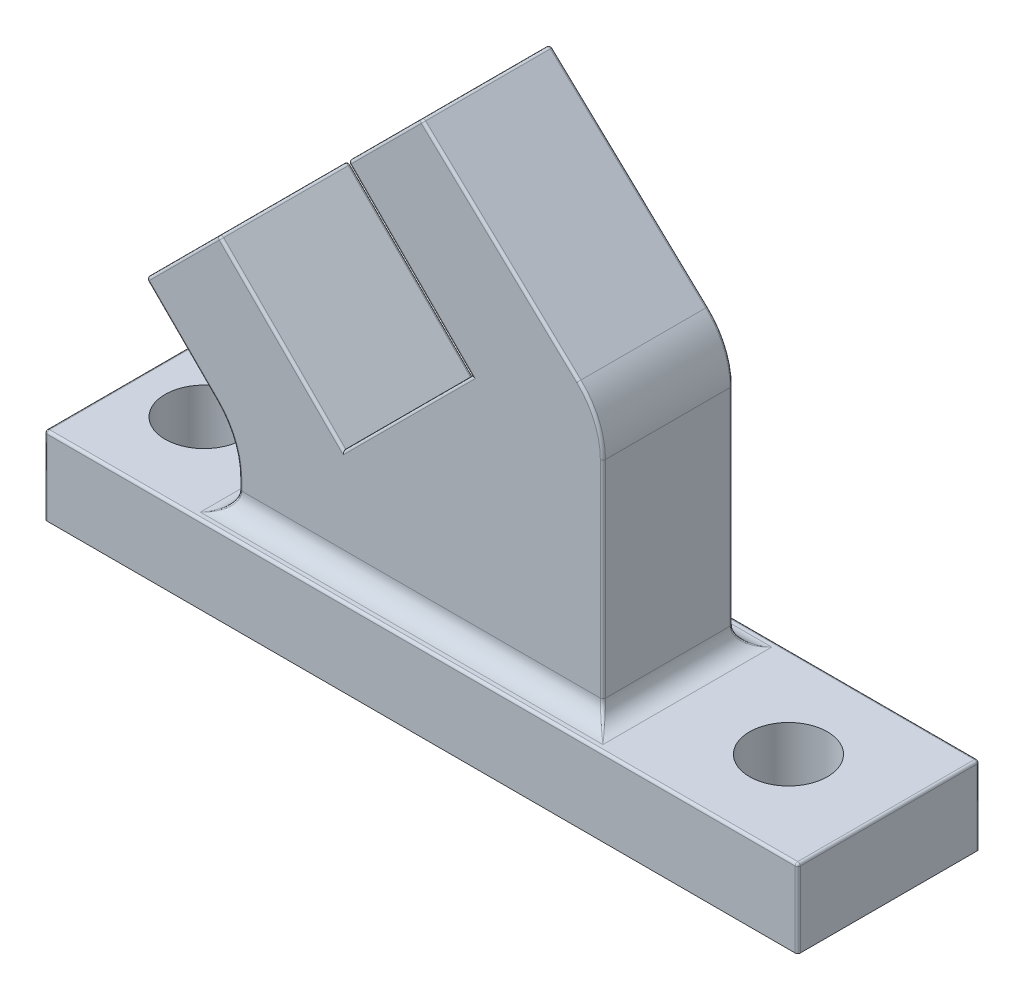
SolidWorks part; units mm, degrees
material "6061-T6 (SS)"
ref_plane "Front Plane" through (0, 0, 0) normal (0, 0, 1) x (1, 0, 0)
ref_plane "Top Plane" through (0, 0, 0) normal (0, 1, 0) x (1, 0, 0)
ref_plane "Right Plane" through (0, 0, 0) normal (1, 0, 0) x (0, 0, -1)
sketch "Sketch1" plane through (0, 0, 0) normal (0, 1, 0) x (1, 0, 0)
  line L1 (29, -7) -> (-29, -7)
  line L2 (29, -7) -> (29, 7)
  line L3 (29, 7) -> (-29, 7)
  line L4 (-29, -7) -> (-29, 7)
  line L5 (29, -7) -> (-29, 7) construction
  line L6 (29, 7) -> (-29, -7) construction
  circle A0 centre (-23.71, 0) radius 3
  circle A1 centre (21.29, 0) radius 3
  point P0 (0, 0)
  dimension "D3" = 6
  dimension "D1" = 58
  dimension "D2" = 14
  dimension "D4" = 45
  dimension "D5" = 7.71
extrude "Boss-Extrude1" add sketch "Sketch1" along normal blind 6
sketch "Sketch2" plane through (0, 0, 0) normal (0, 0, 1) x (1, 0, 0)
  line L1 (-29, 6) -> (29, 6) construction
  line L2 (12, 26) -> (-1.9896, 39.2028)
  line L9 (-16, 6) -> (12, 6)
  line L10 (-8, 24) -> (10, 6) construction
  line L11 (-8, 0) -> (-8, 24) construction
  line L12 (-29, 0) -> (29, 0) construction
  line L13 (29, 6) -> (29, 0) construction
  line L14 (12, 6) -> (12, 26)
  line L15 (-8, 14.1005) -> (1.8995, 24)
  line L16 (-8, 14.1005) -> (-17.5459, 23.6464)
  line L17 (-29, 6) -> (-29, 0) construction
  line L19 (1.8995, 24) -> (-7.6464, 33.5459)
  line L20 (-7.6464, 33.5459) -> (-1.9896, 39.2028)
  line L21 (-17.5459, 23.6464) -> (-23.2028, 17.9896)
  line L22 (-23.2028, 17.9896) -> (-17.7574, 12.5442)
  line L24 (-16, 8.3015) -> (-16, 6)
  circle A1 centre (-8, 24) radius 5 construction
  arc A2 (-17.7574, 12.5442) -> (-16, 8.3015) centre (-22, 8.3015) cw
  dimension "D9" = 18
  dimension "D11" = 10
  dimension "D14" = 6
  dimension "D2" = 7
  dimension "D3" = 45
  dimension "D4" = 21
  dimension "D5" = 17
  dimension "D6" = 7
  dimension "D7" = 13.5
  dimension "D8" = 20
  dimension "D10" = 8
  dimension "D12" = 8
  dimension "D13" = 13
extrude "Boss-Extrude2" add sketch "Sketch2" along normal mid plane 10
hole_wizard "M4x0.7 Tapped Hole1" positions "Sketch3" profile "Sketch4" tap size "M4x0.7" standard "ANSI Metric"
sketch "Sketch3" plane through (-20.5962, 20.5962, 0) normal (-0.7071, 0.7071, 0) x (0.7071, 0.7071, 0)
  line L2 (4.3137, 0) -> (-3.6863, 0) construction
  line L3 (18.3137, 0) -> (26.3137, 0) construction
  point P0 (-0.6863, 0)
  point P4 (23.3137, 0)
  dimension "D1" = 12
  dimension "D2" = 12
sketch "Sketch4" plane through (-21.0815, 20.1109, 0) normal (0, 0, 1) x (-0.7071, -0.7071, 0)
  line L0 (0, 0) -> (0, 9.9914)
  line L1 (0, 9.9914) -> (1.65, 9)
  line L2 (1.65, 9) -> (1.65, 0)
  line L5 (1.65, 0) -> (0, 0)
  line L10 (0, 9.9914) -> (-1.65, 9) construction
  line L11 (0, -6.35) -> (0, 107.95) construction
  dimension "Tap Drill Dia." = 3.3
  dimension "Tap Drill Depth" = 9
  dimension "Drill Angle" = 118
cosmetic thread "Hole Thread1" parameters "D1"=8, "D2"=4
cosmetic thread "Hole Thread2" parameters "D1"=8, "D2"=4
fillet "Fillet1" radius 6 1 edges at (12, 26, 0)
fillet "Fillet2" radius 1.5 4 edges at (-2, 6, -5) (-16, 6, 0) (-2, 6, 5) (12, 6, 0)
fillet "Fillet3" radius 0.2 38 edges at (-16.4393, 6.4393, -5.4393) (-16, 7.9008, -5) (-16.4567, 10.5976, -5) (-16.4393, 6.4393, 5.4393) (-16, 7.9008, 5) (-16.4567, 10.5976, 5) (12.4393, 6.4393, -5.4393) (4.0643, 33.4894, -5) (11.5095, 25.7885, -5) (12.4393, 6.4393, 5.4393) (4.0643, 33.4894, 5) (11.5095, 25.7885, 5) (29, 3, 7) (29, 3, -7) (29, 6, 0) (0, 6, 7) (0, 6, -7) (-29, 3, 7) (-29, 6, 0) (-29, 3, -7) (-2.8735, 28.773, 5) (-3.0503, 19.0503, 5) (-12.773, 18.8735, 5) (-20.3744, 20.818, 5) (-17.5459, 23.6464, 0) (-7.6464, 33.5459, 0) (-4.818, 36.3744, 5) (-1.9896, 39.2028, 0) (-4.818, 36.3744, -5) (-2.8735, 28.773, -5) (-3.0503, 19.0503, -5) (-12.773, 18.8735, -5) (-20.3744, 20.818, -5) (-23.2028, 17.9896, 0) (-20.4801, 15.2669, -5) (-20.4801, 15.2669, 5) (12, 15.4562, -5) (12, 15.4562, 5)
